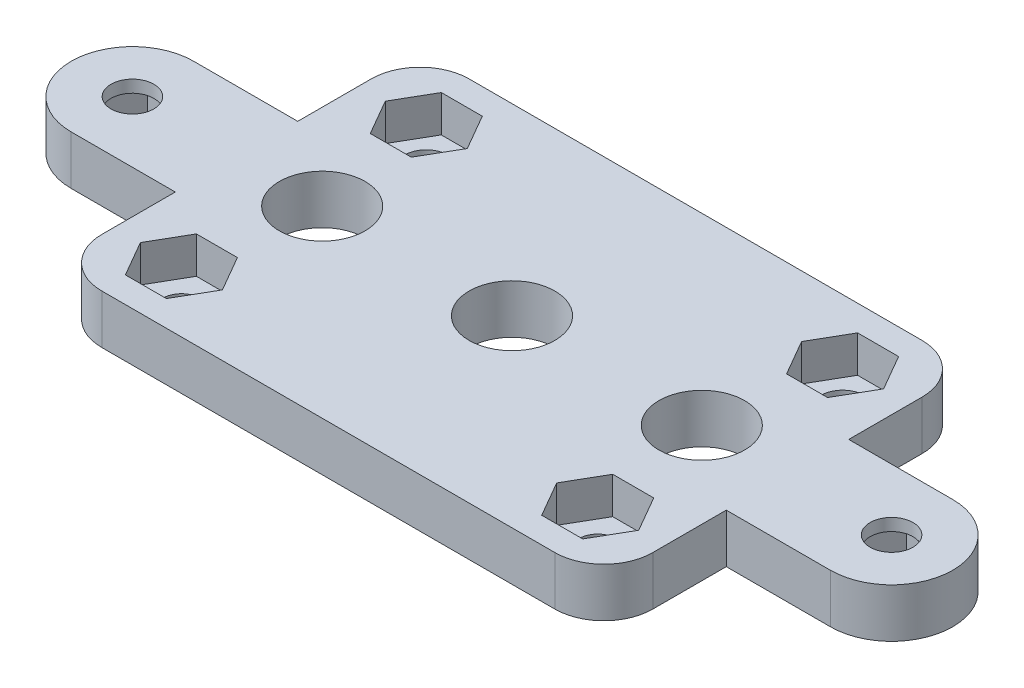
SolidWorks part; units mm, degrees
ref_plane "Plano frontal" through (0, 0, 0) normal (0, 0, 1) x (1, 0, 0)
ref_plane "Plano superior" through (0, 0, 0) normal (0, 1, 0) x (1, 0, 0)
ref_plane "Plano direito" through (0, 0, 0) normal (1, 0, 0) x (0, 0, -1)
sketch "Esboço2" plane through (0, 0, 0) normal (0, 1, 0) x (1, 0, 0)
  line L0 (0, 0) -> (0, 7.9416) construction
  line L1 (-17, -10) -> (17, -10) construction
  line L2 (-17, -10) -> (-17, 10) construction
  line L3 (-17, 10) -> (17, 10) construction
  line L4 (17, -10) -> (17, 10) construction
  line L5 (-17, -10) -> (17, 10) construction
  line L6 (-17, 10) -> (17, -10) construction
  line L7 (0, 0) -> (31, 0) construction
  line L8 (-22.5, -15) -> (22.5, -15)
  line L9 (-22.5, -15) -> (-22.5, -5)
  line L10 (-22.5, 15) -> (22.5, 15)
  line L11 (22.5, -15) -> (22.5, -5)
  line L12 (-22.5, -15) -> (22.5, 15) construction
  line L13 (-22.5, 15) -> (22.5, -15) construction
  line L14 (31, -5) -> (22.5, -5)
  line L15 (31, 5) -> (22.5, 5)
  line L16 (22.5, 5) -> (22.5, 15)
  line L17 (-31, -5) -> (-22.5, -5)
  line L18 (-31, 5) -> (-22.5, 5)
  line L19 (-22.5, 5) -> (-22.5, 15)
  circle A0 centre (17, 10) radius 1.75
  circle A1 centre (17, -10) radius 1.5
  circle A2 centre (-17, -10) radius 1.5
  circle A3 centre (-17, 10) radius 1.75
  arc A4 (31, -5) -> (31, 5) centre (31, 0) ccw
  circle A5 centre (31, 0) radius 1.75
  circle A6 centre (-31, 0) radius 1.75
  arc A7 (-31, -5) -> (-31, 5) centre (-31, 0) cw
  circle A8 centre (0, 0) radius 3.5
  circle A9 centre (15.5, 0) radius 3.5
  circle A10 centre (-15.5, 0) radius 3.5
  point P0 (0, 0)
  dimension "D3" = 3.5
  dimension "D4" = 3
  dimension "D8" = 10
  dimension "D9" = 3.5
  dimension "D10" = 7
  dimension "D11" = 7
  dimension "D1" = 34
  dimension "D2" = 20
  dimension "D5" = 30
  dimension "D6" = 45
  dimension "D7" = 31
extrude "Ressalto-extrusão1" add sketch "Esboço2" along normal blind 4
sketch "Esboço3" plane through (0, 4, 0) normal (0, 1, 0) x (1, 0, 0)
  line L0 (0, 0) -> (0, 4.603) construction
  line L1 (-13.6514, 10) -> (-15.3257, 12.9)
  line L2 (-15.3257, 12.9) -> (-18.6743, 12.9)
  line L3 (-18.6743, 12.9) -> (-20.3486, 10)
  line L4 (-20.3486, 10) -> (-18.6743, 7.1)
  line L5 (-18.6743, 7.1) -> (-15.3257, 7.1)
  line L6 (-15.3257, 7.1) -> (-13.6514, 10)
  line L7 (0, 0) -> (-4.1349, 0) construction
  line L8 (-20.3486, -10) -> (-18.6743, -7.1)
  line L9 (-18.6743, -12.9) -> (-20.3486, -10)
  line L10 (-15.3257, -12.9) -> (-18.6743, -12.9)
  line L11 (-13.6514, -10) -> (-15.3257, -12.9)
  line L12 (-15.3257, -7.1) -> (-13.6514, -10)
  line L13 (-18.6743, -7.1) -> (-15.3257, -7.1)
  line L14 (18.6743, -7.1) -> (15.3257, -7.1)
  line L15 (15.3257, -7.1) -> (13.6514, -10)
  line L16 (13.6514, -10) -> (15.3257, -12.9)
  line L17 (15.3257, -12.9) -> (18.6743, -12.9)
  line L18 (18.6743, -12.9) -> (20.3486, -10)
  line L19 (20.3486, -10) -> (18.6743, -7.1)
  line L20 (15.3257, 7.1) -> (13.6514, 10)
  line L21 (18.6743, 7.1) -> (15.3257, 7.1)
  line L22 (20.3486, 10) -> (18.6743, 7.1)
  line L23 (18.6743, 12.9) -> (20.3486, 10)
  line L24 (15.3257, 12.9) -> (18.6743, 12.9)
  line L25 (13.6514, 10) -> (15.3257, 12.9)
  circle A0 centre (-17, 10) radius 2.9 construction
  circle A1 centre (17, 10) radius 2.9 construction
  dimension "D1" = 5.8
extrude "Corte-extrusão1" cut sketch "Esboço3" against normal blind 3
fillet "Filete1" radius 4 4 edges at (-22.5, 2, -15) (-22.5, 2, 15) (22.5, 2, 15) (22.5, 2, -15)
sketch "Esboço6" plane through (0, 0, 0) normal (0, -1, 0) x (1, 0, 0)
  line L0 (0, 0) -> (0, 8.2511) construction
  line L1 (-27.6514, 0) -> (-29.3257, 2.9)
  line L2 (-29.3257, 2.9) -> (-32.6743, 2.9)
  line L3 (-32.6743, 2.9) -> (-34.3486, 0)
  line L4 (-34.3486, 0) -> (-32.6743, -2.9)
  line L5 (-32.6743, -2.9) -> (-29.3257, -2.9)
  line L6 (-29.3257, -2.9) -> (-27.6514, 0)
  line L7 (29.3257, -2.9) -> (27.6514, 0)
  line L8 (32.6743, -2.9) -> (29.3257, -2.9)
  line L9 (34.3486, 0) -> (32.6743, -2.9)
  line L10 (32.6743, 2.9) -> (34.3486, 0)
  line L11 (29.3257, 2.9) -> (32.6743, 2.9)
  line L12 (27.6514, 0) -> (29.3257, 2.9)
  circle A0 centre (-31, 0) radius 2.9 construction
  point P12 (-28.4885, 1.45)
  dimension "D1" = 5.8
extrude "Corte-extrusão2" cut sketch "Esboço6" against normal blind 3
